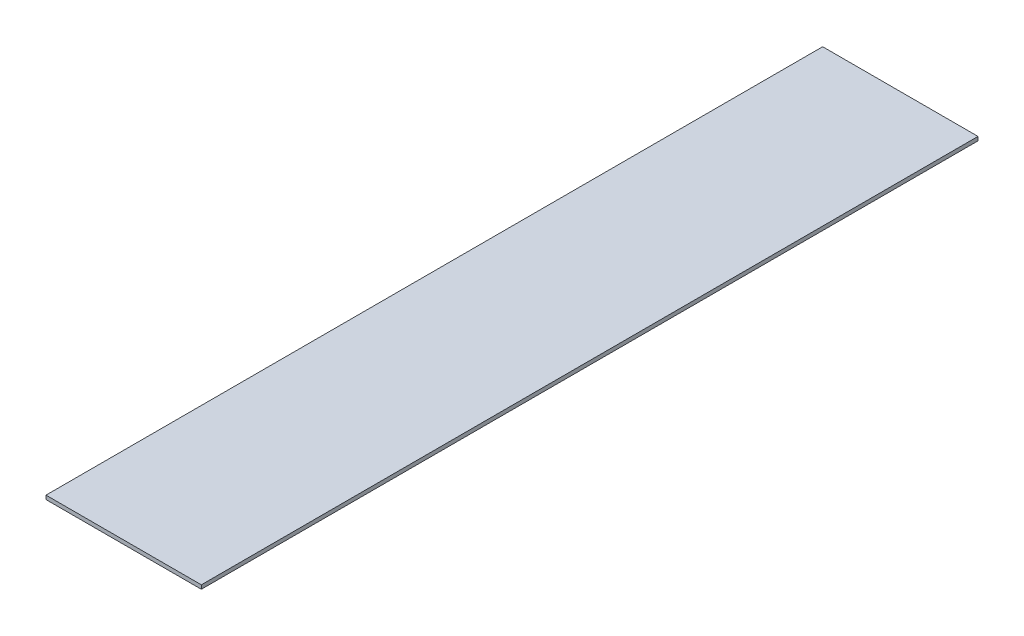
SolidWorks part; units mm, degrees
ref_plane "Front Plane" through (0, 0, 0) normal (0, 0, 1) x (1, 0, 0)
ref_plane "Top Plane" through (0, 0, 0) normal (0, 1, 0) x (1, 0, 0)
ref_plane "Right Plane" through (0, 0, 0) normal (1, 0, 0) x (0, 0, -1)
sketch "Sketch2" plane through (0, 0, 0) normal (0, 1, 0) x (1, 0, 0)
  line L1 (-60, 300) -> (60, 300)
  line L2 (-60, 300) -> (-60, -300)
  line L3 (-60, -300) -> (60, -300)
  line L4 (60, 300) -> (60, -300)
  line L5 (-60, 300) -> (60, -300) construction
  line L6 (-60, -300) -> (60, 300) construction
  point P0 (0, 0)
  dimension "D1" = 600
  dimension "D2" = 120
extrude "Boss-Extrude1" add sketch "Sketch2" along normal blind 3
